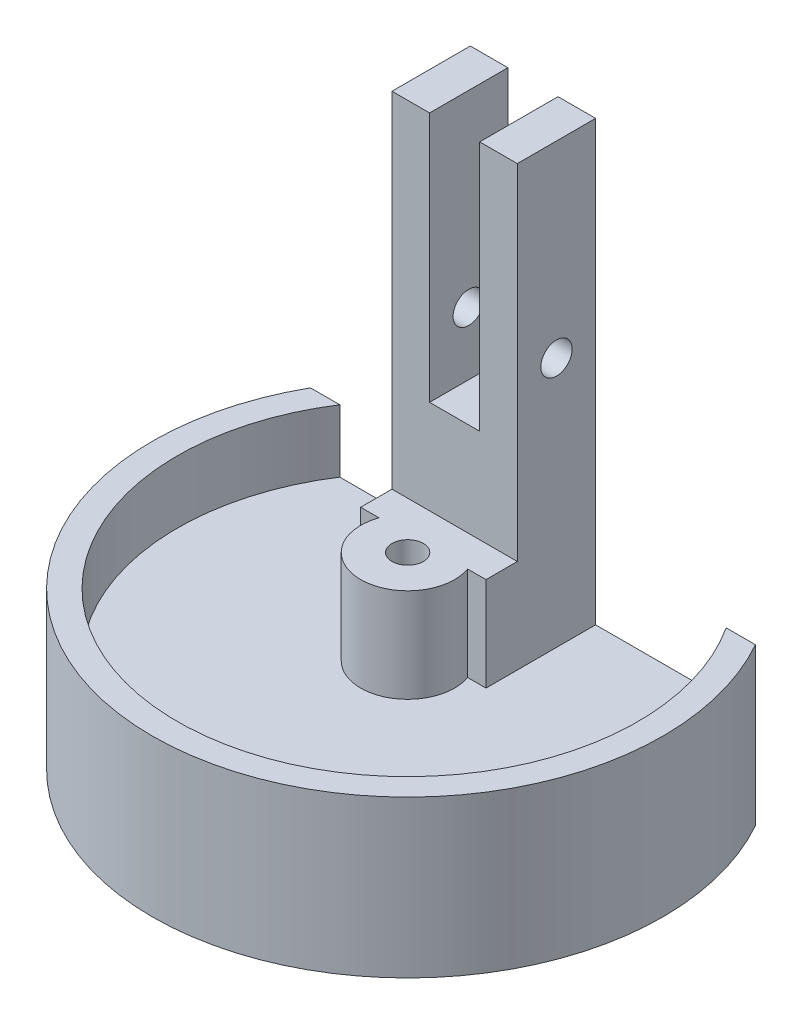
SolidWorks part; units mm, degrees
ref_plane "Спереди" through (0, 0, 0) normal (0, 0, 1) x (1, 0, 0)
ref_plane "Сверху" through (0, 0, 0) normal (0, 1, 0) x (1, 0, 0)
ref_plane "Справа" through (0, 0, 0) normal (1, 0, 0) x (0, 0, -1)
sketch "Эскиз1" plane through (0, 0, 0) normal (0, 1, 0) x (1, 0, 0)
  circle A0 centre (0, 0) radius 2.5
  circle A1 centre (0, 0) radius 7.5
  dimension "D1" = 15
  dimension "D2" = 5
extrude "Вытянуть1" add sketch "Эскиз1" along normal blind 20
sketch "Эскиз2" plane through (0, 0, 0) normal (0, 1, 0) x (1, 0, 0)
  circle A0 centre (0, 0) radius 40.75
  circle A1 centre (0, 0) radius 2.5
  dimension "D1" = 81.5
  dimension "D2" = 5
extrude "Вытянуть2" add sketch "Эскиз2" along normal blind 5
sketch "Эскиз3" plane through (0, 5, 0) normal (0, 1, 0) x (1, 0, 0)
  circle A0 centre (0, 0) radius 36.75
  circle A1 centre (0, 0) radius 40.75
  circle A2 centre (0, 0) radius 40.75 construction
  dimension "D1" = 73.5
extrude "t" add sketch "Эскиз3" along normal blind 10 and the other way blind 15
sketch "Эскиз4" plane through (0, 5, 0) normal (0, 1, 0) x (1, 0, 0)
  line L1 (-10, 2.5) -> (10, 2.5)
  line L2 (-10, 2.5) -> (-10, 20)
  line L3 (-10, 20) -> (10, 20)
  line L4 (10, 2.5) -> (10, 20)
  circle A1 centre (0, 0) radius 2.5 construction
  point P4 (0, 2.5)
  dimension "D1" = 20
  dimension "D2" = 20
extrude "Вытянуть4" add sketch "Эскиз4" along normal blind 70
sketch "Эскиз6" plane through (0, 75, 0) normal (0, 1, 0) x (1, 0, 0)
  line L0 (10, 20) -> (-10, 20) construction
  line L1 (-4, 20) -> (4, 20)
  line L2 (-4, 20) -> (-4, 2.5)
  line L3 (-4, 2.5) -> (4, 2.5)
  line L4 (4, 20) -> (4, 2.5)
  line L5 (40.6732, 2.5) -> (-40.6732, 2.5) construction
  line L6 (0, 0) -> (0, -39.8296) construction
  point P9 (0, 20)
  dimension "D1" = 8
extrude "Вытянуть5" cut sketch "Эскиз6" against normal blind 40
sketch "Эскиз7" plane through (10, 0, 0) normal (1, 0, 0) x (0, 0, -1)
  line L4 (20, 75) -> (20, 5) construction
  line L5 (2.5, 75) -> (20, 75) construction
  circle A0 centre (13.75, 45) radius 2.5
  dimension "D3" = 5
  dimension "D1" = 6.25
  dimension "D2" = 30
extrude "Вытянуть6" cut sketch "Эскиз7" against normal up to surface (20 mm away) up to face at (-10, 40, -11.25)
sketch "Эскиз8" plane through (0, 0, 0) normal (0, 1, 0) x (1, 0, 0)
  line L1 (-35.5044, 40.75) -> (35.5044, 40.75)
  line L2 (-35.5044, 40.75) -> (-35.5044, 20)
  line L3 (-35.5044, 20) -> (35.5044, 20)
  line L4 (35.5044, 40.75) -> (35.5044, 20)
  circle A0 centre (0, 0) radius 40.75 construction
  dimension "D1" = 20
extrude "Вытянуть7" cut sketch "Эскиз8" along normal up to next and the other way up to next
sketch "Эскиз9" plane through (0, 75, 0) normal (0, 1, 0) x (1, 0, 0)
  line L0 (10, 2.5) -> (10, 20) construction
  line L1 (-10, 2.5) -> (10, 2.5)
  line L2 (-10, 2.5) -> (-10, 7.5)
  line L3 (-10, 7.5) -> (10, 7.5)
  line L4 (10, 2.5) -> (10, 7.5)
  dimension "D2" = 5
extrude "Вытянуть8" cut sketch "Эскиз9" against normal up to surface (55 mm away)
